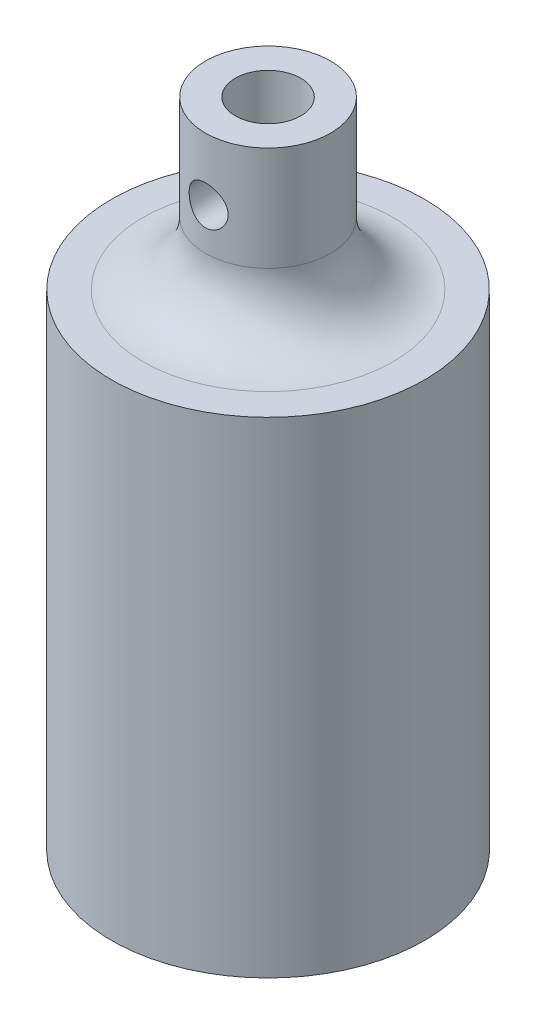
SolidWorks part; units mm, degrees
ref_plane "Front Plane" through (0, 0, 0) normal (0, 0, 1) x (1, 0, 0)
ref_plane "Top Plane" through (0, 0, 0) normal (0, 1, 0) x (1, 0, 0)
ref_plane "Right Plane" through (0, 0, 0) normal (1, 0, 0) x (0, 0, -1)
sketch "Sketch1" plane through (0, 0, 0) normal (0, 1, 0) x (1, 0, 0)
  circle A0 centre (0, 0) radius 9.5377
  dimension "D1" = 19.0754
extrude "Boss-Extrude1" add sketch "Sketch1" along normal blind 29.591 contours A0
sketch "Sketch2" plane through (0, 29.591, 0) normal (0, 1, 0) x (1, 0, 0)
  circle A0 centre (0, 0) radius 3.81
extrude "Boss-Extrude2" add sketch "Sketch2" along normal blind 10.16
sketch "Sketch3" plane through (0, 39.751, 0) normal (0, 1, 0) x (1, 0, 0)
  circle A0 centre (0, 0) radius 1.9939
extrude "Cut-Extrude1" cut sketch "Sketch3" against normal blind 12.7
sketch "Sketch4" plane through (0, 0, 0) normal (0, -1, 0) x (1, 0, 0)
  circle A0 centre (0, 0) radius 8.4836
extrude "Cut-Extrude2" cut sketch "Sketch4" against normal blind 27.94
fillet "Fillet1" radius 3.81 1 edges at (0, 29.591, 3.81)
ref_plane "Plane1" through (0, 0, 9.5377) normal (0, 0, 1) x (1, 0, 0)
hole_wizard "#4-48 Tapped Hole2" positions "Sketch6" profile "Sketch5" tap size "#4-48" standard "ANSI Inch"
sketch "Sketch6" plane through (0, 0, 9.5377) normal (0, 0, 1) x (1, 0, 0)
  line L0 (3.81, 39.751) -> (-3.81, 39.751) construction
  point P2 (0, 35.941)
  dimension "D1" = 3.81
sketch "Sketch5" plane through (0, 35.941, 9.5377) normal (1, 0, 0) x (0, -1, 0)
  line L0 (0, 0) -> (0, 9.6035)
  line L1 (0, 9.6035) -> (1.1874, 8.89)
  line L2 (1.1874, 8.89) -> (1.1874, 0)
  line L5 (1.1874, 0) -> (0, 0)
  line L10 (0, 9.6035) -> (-1.1875, 8.89) construction
  line L11 (0, -6.35) -> (0, 107.95) construction
  dimension "Tap Drill Dia." = 2.3749
  dimension "Tap Drill Depth" = 8.89
  dimension "Drill Angle" = 118
cosmetic thread "Hole Thread1" parameters "D1"=5.588, "D2"=2.8448
